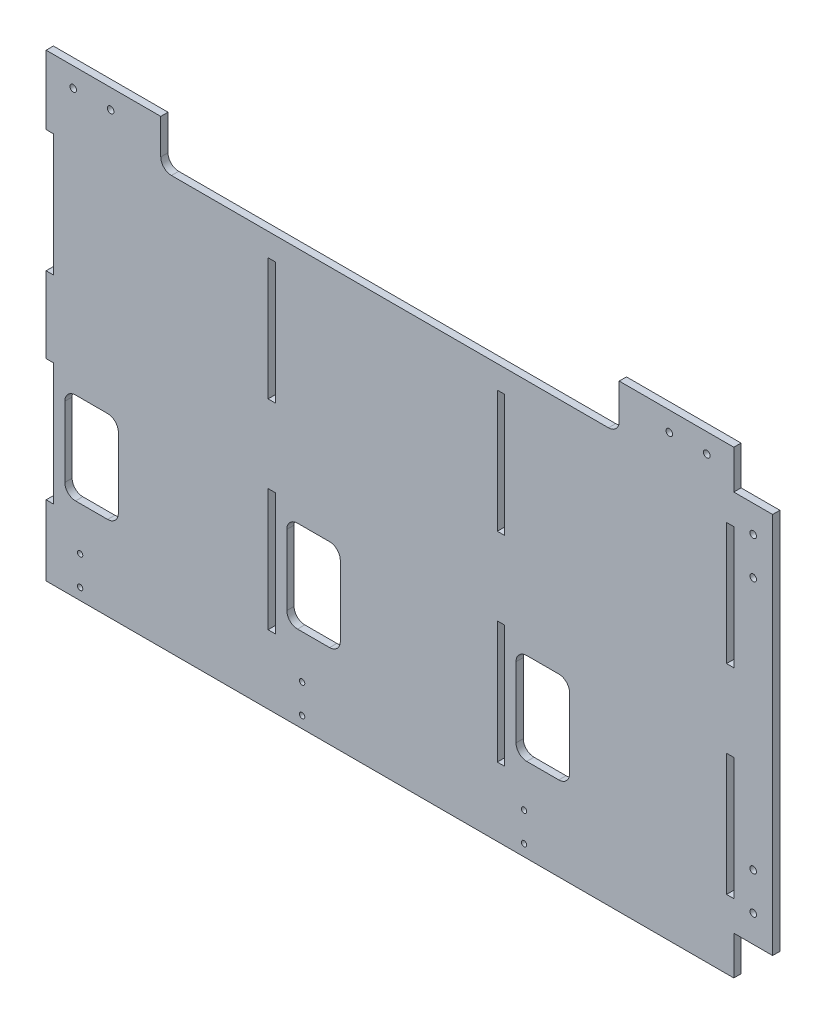
SolidWorks part; units mm, degrees
ref_plane "前基準面" through (0, 0, 0) normal (0, 0, 1) x (1, 0, 0)
ref_plane "上基準面" through (0, 0, 0) normal (0, 1, 0) x (1, 0, 0)
ref_plane "右基準面" through (0, 0, 0) normal (1, 0, 0) x (0, 0, -1)
sketch "草圖1" plane through (0, 0, 0) normal (0, 0, 1) x (1, 0, 0)
  line L1 (-250.4, 150.4) -> (250.4, 150.4)
  line L2 (-250.4, 150.4) -> (-250.4, -150.4)
  line L3 (-250.4, -150.4) -> (250.4, -150.4)
  line L4 (250.4, 150.4) -> (250.4, -150.4)
  line L5 (-250.4, 150.4) -> (250.4, -150.4) construction
  line L6 (-250.4, -150.4) -> (250.4, 150.4) construction
  point P0 (0, 0)
  dimension "D1" = 500.8
  dimension "D2" = 300.8
extrude "填料-伸長1" add sketch "草圖1" along normal blind 4.75 contours L1 L4 L3 L2
sketch "草圖2" plane through (0, 0, 0) normal (0, 0, -1) x (-1, 0, 0)
  line L0 (-225, 125) -> (-225, -125) construction
  line L1 (-250.4, 150.4) -> (-225, 150.4)
  line L2 (-250.4, 150.4) -> (-250.4, 125)
  line L3 (-250.4, 125) -> (-225, 125)
  line L4 (-225, 150.4) -> (-225, 125)
  line L5 (-250.4, -150.4) -> (-225, -150.4)
  line L6 (-250.4, -150.4) -> (-250.4, -125)
  line L7 (-250.4, -125) -> (-225, -125)
  line L8 (-225, -150.4) -> (-225, -125)
  line L9 (250.4, 150.4) -> (225, 150.4)
  line L10 (250.4, 150.4) -> (250.4, 125)
  line L12 (225, 150.4) -> (225, 125)
  line L13 (250.4, -150.4) -> (225, -150.4)
  line L14 (250.4, -150.4) -> (250.4, -125)
  line L16 (225, -150.4) -> (225, -125)
  line L17 (225, 125) -> (225, -125) construction
  line L18 (250.4, 150.4) -> (-250.4, 150.4) construction
  line L19 (-225, 105.4) -> (-220.25, 105.4)
  line L20 (-225, 105.4) -> (-225, 25.4)
  line L21 (-225, 25.4) -> (-220.25, 25.4)
  line L22 (-220.25, 105.4) -> (-220.25, 25.4)
  line L23 (-225, -25.4) -> (-220.25, -25.4)
  line L24 (-225, -25.4) -> (-225, -105.4)
  line L25 (-225, -105.4) -> (-220.25, -105.4)
  line L26 (-220.25, -25.4) -> (-220.25, -105.4)
  line L27 (250.4, -150.4) -> (-250.4, -150.4) construction
  line L44 (225, 105.4) -> (225, 25.4)
  line L45 (225, 105.4) -> (220.25, 105.4)
  line L46 (220.25, 105.4) -> (220.25, 25.4)
  line L47 (225, 25.4) -> (220.25, 25.4)
  line L48 (225, -24.4) -> (225, -104.4)
  line L49 (225, -24.4) -> (220.25, -24.4)
  line L50 (220.25, -24.4) -> (220.25, -104.4)
  line L51 (225, -104.4) -> (220.25, -104.4)
  line L60 (-75, 105.4) -> (-75, 25.4)
  line L61 (-75, 25.4) -> (-70.25, 25.4)
  line L62 (-70.25, 105.4) -> (-70.25, 25.4)
  line L63 (-75, 105.4) -> (-70.25, 105.4)
  line L80 (75, 105.4) -> (75, 25.4)
  line L81 (75, 25.4) -> (79.75, 25.4)
  line L82 (79.75, 105.4) -> (79.75, 25.4)
  line L83 (75, 105.4) -> (79.75, 105.4)
  line L84 (-250.4, 0) -> (250.4, 0) construction
  line L85 (-250.4, 150.4) -> (-250.4, -150.4) construction
  line L86 (250.4, 150.4) -> (250.4, -150.4) construction
  line L89 (250.4, -125) -> (250.4, 125)
  line L91 (250.4, 125) -> (250.4, -125)
  line L92 (75, -105.4) -> (79.75, -105.4)
  line L93 (79.75, -105.4) -> (79.75, -25.4)
  line L94 (75, -25.4) -> (79.75, -25.4)
  line L95 (75, -105.4) -> (75, -25.4)
  line L105 (-75, -105.4) -> (-70.25, -105.4)
  line L106 (-70.25, -105.4) -> (-70.25, -25.4)
  line L107 (-75, -25.4) -> (-70.25, -25.4)
  line L108 (-75, -105.4) -> (-75, -25.4)
  line L112 (250.4, 125) -> (250.4, -125)
  line L113 (250.4, -150.4) -> (225, -150.4)
  line L114 (250.4, -150.4) -> (250.4, 150.4)
  line L115 (250.4, 150.4) -> (225, 150.4)
  line L116 (225, -150.4) -> (225, 150.4)
  dimension "D1" = 25.4
  dimension "D2" = 25.4
  dimension "D3" = 25.4
  dimension "D4" = 25.4
  dimension "D6" = 25.4
  dimension "D7" = 25.4
  dimension "D8" = 25.4
  dimension "D9" = 4.75
  dimension "D10" = 80
  dimension "D11" = 45
  dimension "D12" = 4.75
  dimension "D13" = 80
  dimension "D14" = 45
  dimension "D15" = 80
  dimension "D16" = 25.4
  dimension "D17" = 25.4
  dimension "D18" = 4.75
  dimension "D19" = 250
  dimension "D20" = 25.4
  dimension "D21" = 4.75
extrude "除料-伸長1" cut sketch "草圖2" against normal blind 25.4
sketch "草圖3" plane through (0, 0, 4.75) normal (0, 0, 1) x (1, 0, 0)
  circle A0 centre (-207.3, 137.7) radius 2.15
  circle A1 centre (-182.8, 137.7) radius 2.15
  circle A2 centre (182.8, 137.7) radius 2.15
  circle A3 centre (207.3, 137.7) radius 2.15
  circle A4 centre (237.7, 107.3) radius 2.15
  circle A5 centre (237.7, 82.8) radius 2.15
  circle A6 centre (237.7, -82.8) radius 2.15
  circle A7 centre (237.7, -107.3) radius 2.15
  circle A12 centre (-237.7, 107.3) radius 2.15
  circle A13 centre (-237.7, 82.8) radius 2.15
  circle A14 centre (-237.7, -82.8) radius 2.15
  circle A15 centre (-237.7, -107.3) radius 2.15
  dimension "D1" = 2
extrude "除料-伸長2" cut sketch "草圖3" against normal blind 5
sketch "草圖5" plane through (0, 0, 4.75) normal (0, 0, 1) x (1, 0, 0)
  line L0 (-75, 25.4) -> (-75, 105.4) construction
  line L1 (82.5, -35.4) -> (117.5, -35.4)
  line L2 (82.5, -35.4) -> (82.5, -95.4)
  line L3 (82.5, -95.4) -> (117.5, -95.4)
  line L4 (117.5, -35.4) -> (117.5, -95.4)
  line L5 (82.5, -35.4) -> (117.5, -95.4) construction
  line L6 (82.5, -95.4) -> (117.5, -35.4) construction
  line L7 (-67.5, -35.4) -> (-32.5, -35.4)
  line L8 (-67.5, -35.4) -> (-67.5, -95.4)
  line L9 (-67.5, -95.4) -> (-32.5, -95.4)
  line L10 (-32.5, -35.4) -> (-32.5, -95.4)
  line L11 (-67.5, -35.4) -> (-32.5, -95.4) construction
  line L12 (-67.5, -95.4) -> (-32.5, -35.4) construction
  line L13 (-212.75, -35.4) -> (-177.75, -35.4)
  line L14 (-212.75, -35.4) -> (-212.75, -95.4)
  line L15 (-212.75, -95.4) -> (-177.75, -95.4)
  line L16 (-177.75, -35.4) -> (-177.75, -95.4)
  line L17 (-212.75, -35.4) -> (-177.75, -95.4) construction
  line L18 (-212.75, -95.4) -> (-177.75, -35.4) construction
  line L20 (-220.25, -104.4) -> (-220.25, -24.4) construction
  line L21 (75, -25.4) -> (75, -105.4) construction
  line L22 (-225, 150.4) -> (225, 150.4) construction
  line L24 (225, 125) -> (225, 150.4) construction
  line L25 (-150, 150.4) -> (150, 150.4)
  line L26 (-150, 150.4) -> (-150, 120.4)
  line L27 (-150, 120.4) -> (150, 120.4)
  line L28 (150, 150.4) -> (150, 120.4)
  line L29 (-225, -150.4) -> (225, -150.4) construction
  point P0 (100, -65.4)
  point P5 (-50, -65.4)
  point P10 (-195.25, -65.4)
  dimension "D1" = 35
  dimension "D2" = 60
  dimension "D3" = 35
  dimension "D4" = 60
  dimension "D5" = 35
  dimension "D6" = 60
  dimension "D7" = 7.5
  dimension "D8" = 7.5
  dimension "D9" = 55
  dimension "D10" = 55
  dimension "D11" = 55
  dimension "D12" = 7.5
  dimension "D13" = 300
  dimension "D14" = 75
  dimension "D15" = 30
extrude "除料-伸長3" cut sketch "草圖5" against normal blind 10
fillet "圓角1" radius 7 14 edges at (-150, 120.4, 2.375) (150, 120.4, 2.375) (117.5, -35.4, 2.375) (82.5, -35.4, 2.375) (82.5, -95.4, 2.375) (117.5, -95.4, 2.375) (-32.5, -95.4, 2.375) (-67.5, -95.4, 2.375) (-32.5, -35.4, 2.375) (-67.5, -35.4, 2.375) (-177.75, -95.4, 2.375) (-212.75, -95.4, 2.375) (-212.75, -35.4, 2.375) (-177.75, -35.4, 2.375)
sketch "草圖6" plane through (0, 0, 4.75) normal (0, 0, 1) x (1, 0, 0)
  line L1 (-225, -150.4) -> (225, -150.4) construction
  line L2 (-220.25, -104.4) -> (-220.25, -24.4) construction
  circle A0 centre (-202.75, -142.9) radius 1.75
  circle A1 centre (-202.75, -123.9) radius 1.75
  circle A2 centre (-57.5, -142.9) radius 1.75
  circle A3 centre (-57.5, -123.9) radius 1.75
  circle A4 centre (87.75, -142.9) radius 1.75
  circle A5 centre (87.75, -123.9) radius 1.75
  dimension "D3" = 19
  dimension "D5" = 3.5
  dimension "D6" = 3.5
  dimension "D1" = 17.5
  dimension "D2" = 7.5
  dimension "D4" = 3
extrude "除料-伸長4" cut sketch "草圖6" against normal blind 10
